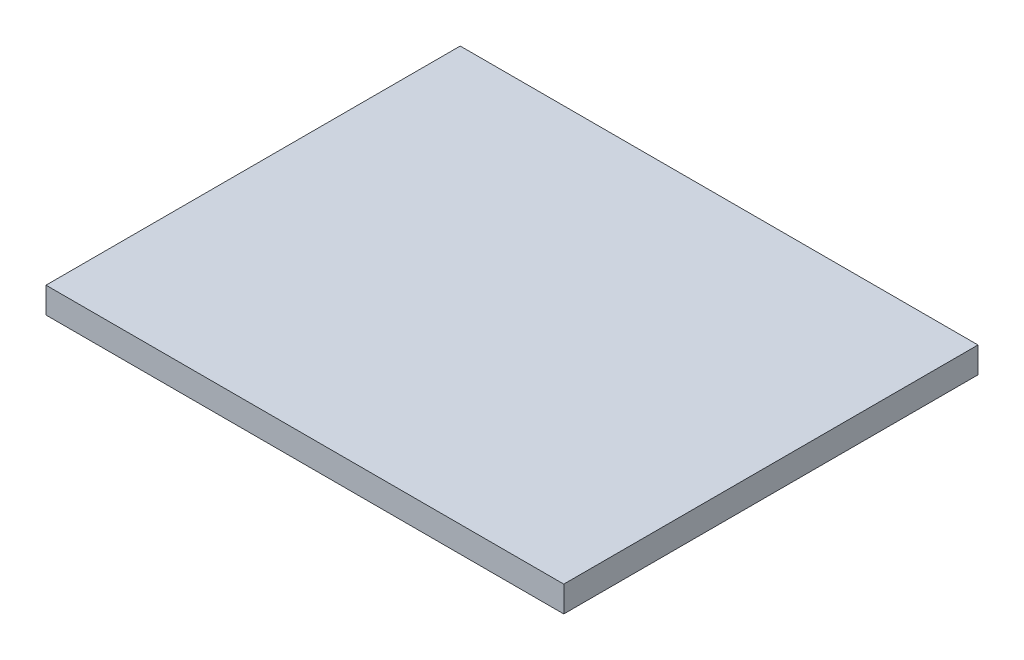
SolidWorks part; units mm, degrees
ref_plane "Plane1" through (0, 0, 0) normal (0, 0, 1) x (1, 0, 0)
ref_plane "Plane2" through (0, 0, 0) normal (0, 1, 0) x (1, 0, 0)
ref_plane "Plane3" through (0, 0, 0) normal (1, 0, 0) x (0, 0, -1)
other "Configuration Table"
sketch "Sketch1" plane through (0, 0, 0) normal (0, 0, 1) x (1, 0, 0)
  line L1 (-50, 5) -> (50, 5)
  line L2 (-50, 5) -> (-50, 0)
  line L3 (-50, 0) -> (50, 0)
  line L4 (50, 5) -> (50, 0)
  dimension "D1" = 5
extrude "Base-Extrude" add sketch "Sketch1" along normal mid plane 80
